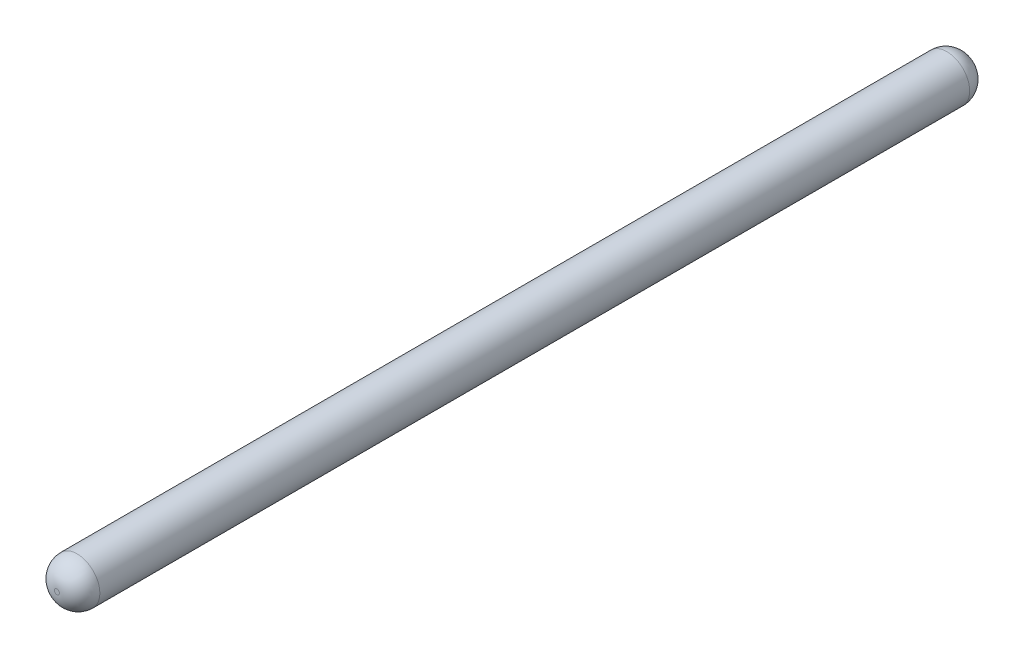
SolidWorks part; units mm, degrees
material "Plain Carbon Steel"
ref_plane "Front Plane" through (0, 0, 0) normal (0, 0, 1) x (1, 0, 0)
ref_plane "Top Plane" through (0, 0, 0) normal (0, 1, 0) x (1, 0, 0)
ref_plane "Right Plane" through (0, 0, 0) normal (1, 0, 0) x (0, 0, -1)
sketch "Sketch1" plane through (0, 0, 0) normal (0, 0, 1) x (1, 0, 0)
  circle A0 centre (0, 0) radius 0.9
  dimension "D1" = 1.8
extrude "Boss-Extrude1" add sketch "Sketch1" along normal blind 36
fillet "Fillet1" radius 0.8 2 edges at (0.9, 0, 0) (0.9, 0, 36)
